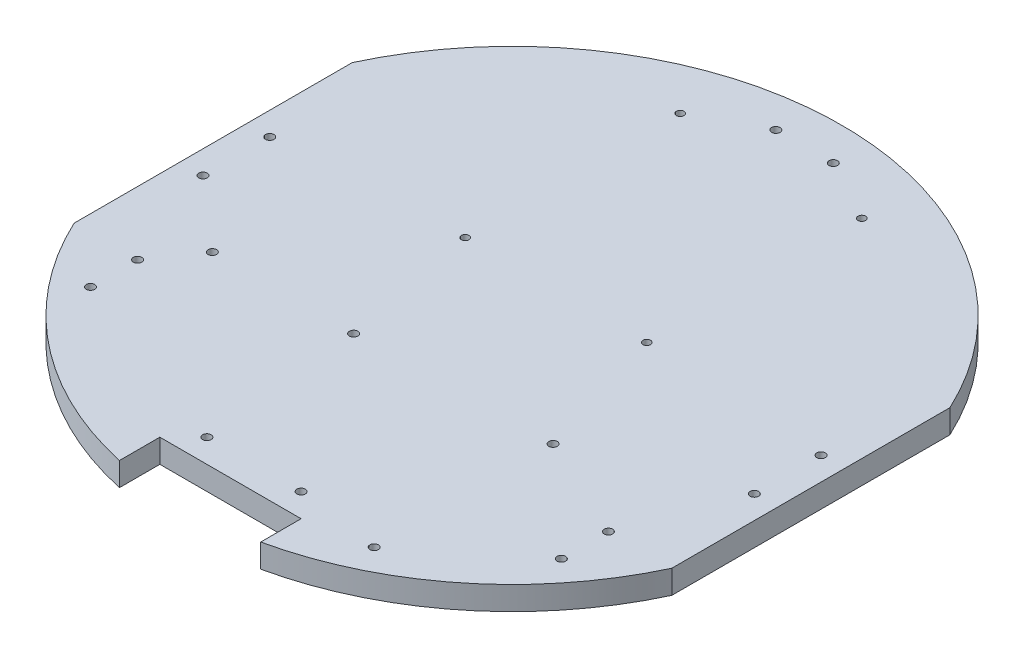
SolidWorks part; units mm, degrees
ref_plane "Front Plane" through (0, 0, 0) normal (0, 0, 1) x (1, 0, 0)
ref_plane "Top Plane" through (0, 0, 0) normal (0, 1, 0) x (1, 0, 0)
ref_plane "Right Plane" through (0, 0, 0) normal (1, 0, 0) x (0, 0, -1)
sketch "Sketch1" plane through (0, 0, 0) normal (0, 1, 0) x (1, 0, 0)
  line L0 (-80.6037, 37.5) -> (-80.6037, -37.5)
  line L1 (0, -88.9) -> (0, 88.9) construction
  line L2 (80.6037, 37.5) -> (80.6037, -37.5)
  arc A0 (-80.6037, -37.5) -> (80.6037, -37.5) centre (0, 0) ccw
  arc A1 (80.6037, 37.5) -> (-80.6037, 37.5) centre (0, 0) ccw
  dimension "D1" = 177.8
  dimension "D2" = 75
extrude "Main Body" add sketch "Sketch1" along normal blind 6.35
sketch "Sketch2" plane through (0, 6.35, 0) normal (0, 1, 0) x (1, 0, 0)
  line L1 (24.5, 69.85) -> (-24.5, 69.85) construction
  line L2 (24.5, 69.85) -> (24.5, 11.85) construction
  line L3 (24.5, 11.85) -> (-24.5, 11.85) construction
  line L4 (-24.5, 69.85) -> (-24.5, 11.85) construction
  line L5 (24.5, 69.85) -> (-24.5, 11.85) construction
  line L6 (24.5, 11.85) -> (-24.5, 69.85) construction
  circle A0 centre (24.5, 69.85) radius 1.025
  circle A1 centre (24.5, 11.85) radius 1.025
  circle A2 centre (-24.5, 11.85) radius 1.025
  circle A3 centre (-24.5, 69.85) radius 1.025
  arc A5 (80.6037, 37.5) -> (-80.6037, 37.5) centre (0, 0) ccw construction
  point P0 (0, 40.85)
  point P11 (0, 88.9)
  dimension "D3" = 2.05
  dimension "D1" = 49
  dimension "D2" = 58
  dimension "D4" = 19.05
extrude "Raspberry Pi" cut sketch "Sketch2" against normal up to next
sketch "Sketch3" plane through (0, 6.35, 0) normal (0, 1, 0) x (1, 0, 0)
  line L0 (-80.6037, 0) -> (80.6037, 0) construction
  line L1 (-80.6037, 37.5) -> (-80.6037, -37.5) construction
  line L2 (80.6037, -37.5) -> (80.6037, 37.5) construction
  line L3 (-74.3537, -9) -> (-74.3537, 9) construction
  line L4 (0, -88.9) -> (0, 88.9) construction
  line L5 (74.3537, -9) -> (74.3537, 9) construction
  circle A0 centre (-74.3537, 9) radius 1.143
  circle A1 centre (-74.3537, -9) radius 1.143
  arc A2 (-80.6037, -37.5) -> (80.6037, -37.5) centre (0, 0) ccw construction
  arc A3 (80.6037, 37.5) -> (-80.6037, 37.5) centre (0, 0) ccw construction
  circle A4 centre (74.3537, 9) radius 1.143
  circle A5 centre (74.3537, -9) radius 1.143
  point P10 (-74.3537, 0)
  point P19 (74.3537, 0)
  dimension "D1" = 6.25
  dimension "D2" = 2.286
  dimension "D3" = 18
extrude "Motor Mounts" cut sketch "Sketch3" against normal up to next
sketch "Sketch4" plane through (0, 6.35, 0) normal (0, 1, 0) x (1, 0, 0)
  line L0 (0, -88.9) -> (0, 88.9) construction
  line L1 (-7.747, 78.9) -> (7.747, 78.9) construction
  arc A0 (-80.6037, -37.5) -> (80.6037, -37.5) centre (0, 0) ccw construction
  arc A1 (80.6037, 37.5) -> (-80.6037, 37.5) centre (0, 0) ccw construction
  circle A2 centre (-7.747, 78.9) radius 1.143
  circle A3 centre (7.747, 78.9) radius 1.143
  point P10 (0, 78.9)
  dimension "D1" = 2.286
  dimension "D2" = 15.494
  dimension "D3" = 10
extrude "Cut-Extrude3" cut sketch "Sketch4" against normal up to next
sketch "Sketch5" plane through (0, 6.35, 0) normal (0, 1, 0) x (1, 0, 0)
  line L0 (0, -88.9) -> (0, 88.9) construction
  line L1 (29.21, -82.5485) -> (29.21, 0.1133) construction
  line L2 (29.21, -24.4861) -> (50029.21, -24.4861) construction
  line L3 (29.21, -28.2961) -> (56.134, -28.2961) construction
  line L4 (29.21, -28.2961) -> (29.21, -68.9361) construction
  line L5 (29.21, -68.9361) -> (56.134, -68.9361) construction
  line L6 (56.134, -28.2961) -> (56.134, -68.9361) construction
  line L7 (29.21, -72.7461) -> (50029.21, -72.7461) construction
  line L8 (29.21, -28.2961) -> (29.21, -24.4861) construction
  line L9 (29.21, -68.9361) -> (29.21, -72.7461) construction
  line L10 (35.56, -24.4861) -> (35.56, -72.7461) construction
  arc A0 (-80.6037, -37.5) -> (80.6037, -37.5) centre (0, 0) ccw construction
  arc A1 (80.6037, 37.5) -> (-80.6037, 37.5) centre (0, 0) ccw construction
  circle A2 centre (35.56, -24.4861) radius 1.143
  circle A3 centre (35.56, -72.7461) radius 1.143
  dimension "D4" = 2.286
  dimension "D1" = 29.21
  dimension "D2" = 40.64
  dimension "D3" = 26.924
  dimension "D5" = 6.35
  dimension "D6" = 48.26
extrude "Grabber Mount" cut sketch "Sketch5" against normal through all
sketch "Sketch6" plane through (0, 6.35, 0) normal (0, 1, 0) x (1, 0, 0)
  line L0 (0, -88.1692) -> (0, -5.66) construction
  line L2 (-26.543, -75.692) -> (26.543, -75.692) construction
  line L3 (-26.543, -75.692) -> (-26.543, -63.5) construction
  line L4 (-26.543, -63.5) -> (26.543, -63.5) construction
  line L5 (26.543, -75.692) -> (26.543, -63.5) construction
  line L6 (-26.543, -75.692) -> (26.543, -63.5) construction
  line L7 (-26.543, -63.5) -> (26.543, -75.692) construction
  circle A0 centre (-12.7, -69.596) radius 1.143
  circle A1 centre (12.7, -69.596) radius 1.143
  point P1 (0, -69.596)
  dimension "D4" = 2.286
  dimension "D1" = 63.5
  dimension "D2" = 12.192
  dimension "D3" = 53.086
  dimension "D5" = 25.4
  dimension "D6" = 12.7
extrude "Front IR" cut sketch "Sketch6" against normal through all
sketch "Sketch8" plane through (0, 6.35, 0) normal (0, 1, 0) x (1, 0, 0)
  line L0 (0, 0) -> (0, 88.9) construction
  line L1 (-80.6037, 37.5) -> (-80.6037, -37.5) construction
  line L2 (-80.6037, -29.88) -> (80.6037, -29.88) construction
  line L3 (80.6037, -37.5) -> (80.6037, 37.5) construction
  line L4 (-80.6037, 23.206) -> (80.6037, 23.206) construction
  line L5 (0, 23.206) -> (0, -29.88) construction
  line L6 (0, -29.88) -> (0, -3.337) construction
  line L7 (-63.5, -37.5) -> (63.5, -37.5) construction
  circle A1 centre (-63.5, -37.5) radius 1.143
  circle A2 centre (-63.5, -50.2) radius 1.143
  circle A3 centre (63.5, -50.2) radius 1.143
  circle A4 centre (63.5, -37.5) radius 1.143
  dimension "D3" = 2.286
  dimension "D1" = 53.086
  dimension "D2" = 7.62
  dimension "D4" = 12.7
  dimension "D5" = 63.5
  dimension "D6" = 7.62
extrude "Side IR" cut sketch "Sketch8" against normal through all
sketch "Sketch9" plane through (0, 6.35, 0) normal (0, 1, 0) x (1, 0, 0)
  line L0 (35.56, -25.6291) -> (-80.6037, -25.6291) construction
  line L1 (-80.6037, 37.5) -> (-80.6037, -37.5) construction
  circle A0 centre (35.56, -24.4861) radius 1.143 construction
  circle A1 centre (-55.2037, -25.6291) radius 1.143
  circle A2 centre (-17.1037, -25.6291) radius 1.143
  dimension "D1" = 2.286
  dimension "D2" = 38.1
  dimension "D3" = 25.4
extrude "Cut-Extrude4" cut sketch "Sketch9" against normal through all
sketch "Sketch10" plane through (0, 6.35, 0) normal (0, 1, 0) x (1, 0, 0)
  line L0 (0, -88.9) -> (0, 0) construction
  line L1 (19.05, -101.854) -> (19.05, -75.946)
  line L2 (19.05, -101.854) -> (-19.05, -101.854)
  line L3 (19.05, -75.946) -> (-19.05, -75.946)
  line L4 (-19.05, -101.854) -> (-19.05, -75.946)
  line L5 (19.05, -101.854) -> (-19.05, -75.946) construction
  line L6 (19.05, -75.946) -> (-19.05, -101.854) construction
  arc A0 (-80.6037, -37.5) -> (80.6037, -37.5) centre (0, 0) ccw construction
  circle A1 centre (-12.7, -69.596) radius 1.143 construction
  dimension "D2" = 6.35
  dimension "D1" = 38.1
extrude "Cut-Extrude5" cut sketch "Sketch10" against normal through all
